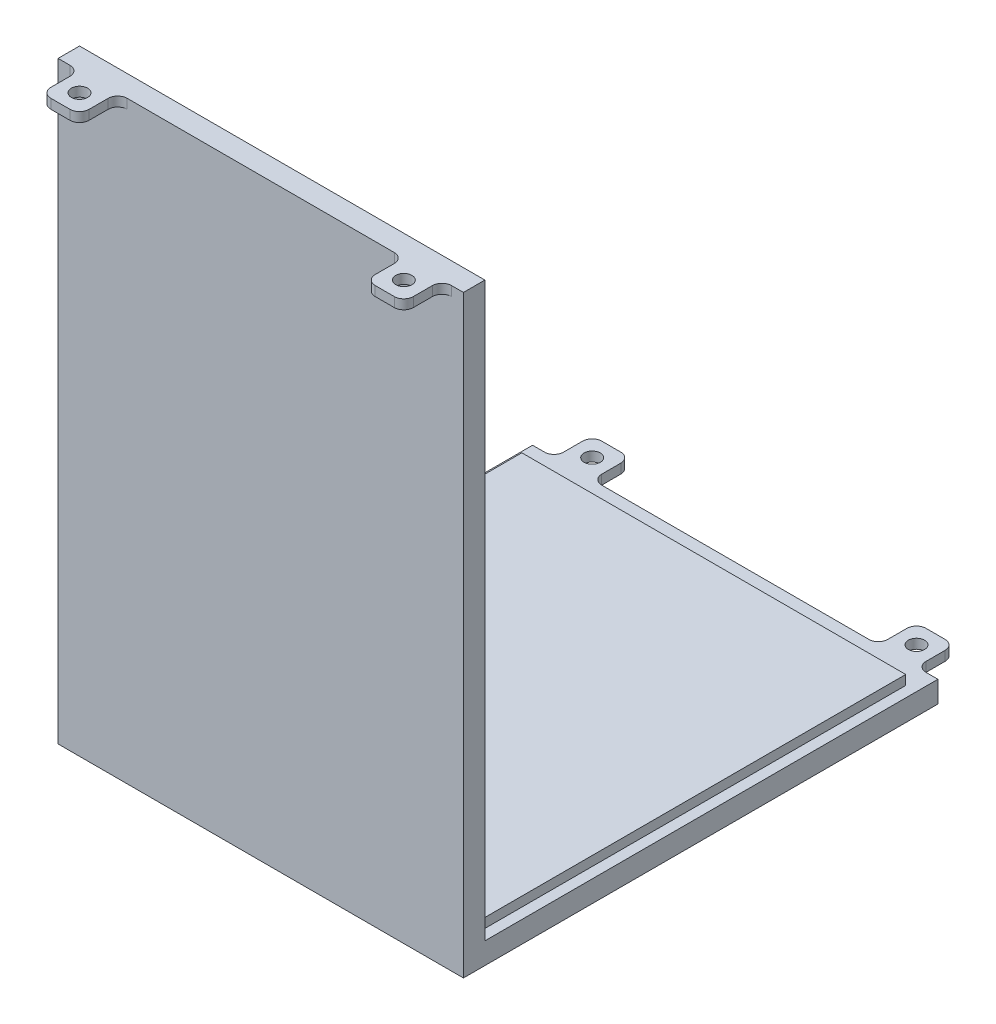
SolidWorks part; units mm, degrees
ref_plane "Front Plane" through (0, 0, 0) normal (1, 0, 0) x (0, 1, 0)
ref_plane "Top Plane" through (0, 0, 0) normal (0, 0, 1) x (0, 1, 0)
ref_plane "Right Plane" through (0, 0, 0) normal (0, 1, 0) x (-1, 0, 0)
sketch "Sketch1" plane through (0, 0, 0) normal (0, 0, 1) x (0, 1, 0)
  line L1 (0, 0) -> (124.5, 0)
  line L2 (0, 0) -> (0, 85)
  line L3 (0, 85) -> (124.5, 85)
  line L4 (124.5, 0) -> (124.5, 85)
  dimension "D1" = 85
  dimension "D2" = 124.5
extrude "Boss-Extrude1" add sketch "Sketch1" along normal blind 4.5
sketch "Sketch2" plane through (0, 0, 0) normal (0, 0, -1) x (1, 0, 0)
  line L0 (0, 0) -> (0, -124.5) construction
  line L1 (-85, 0) -> (0, 0)
  line L2 (-85, 0) -> (-85, -4.5)
  line L3 (-85, -4.5) -> (0, -4.5)
  line L4 (0, 0) -> (0, -4.5)
  dimension "D1" = 4.5
extrude "Boss-Extrude2" add sketch "Sketch2" along normal blind 95
sketch "Sketch3" plane through (0, 0, 0) normal (0, 0, -1) x (1, 0, 0)
  line L0 (-85, -4.5) -> (0, -4.5) construction
  line L1 (-82.75, -4.5) -> (-2.25, -4.5)
  line L2 (-82.75, -4.5) -> (-82.75, -6.5)
  line L3 (-82.75, -6.5) -> (-2.25, -6.5)
  line L4 (-2.25, -4.5) -> (-2.25, -6.5)
  line L5 (-42.5, -124.5) -> (-42.5, -4.5) construction
  line L6 (0, -124.5) -> (-85, -124.5) construction
  line L7 (-85, -124.5) -> (-85, -4.5) construction
  line L8 (0, 0) -> (0, -124.5) construction
  dimension "D1" = 2.25
  dimension "D2" = 2.25
  dimension "D3" = 2
extrude "Boss-Extrude3" add sketch "Sketch3" along normal offset from surface (90.5 mm away) 4.5 up to face at (-42.5, 2.25, -95)
sketch "Sketch4" plane through (0, 0, 4.5) normal (0, 0, 1) x (1, 0, 0)
  line L0 (-42.5, 124.5) -> (-42.5, 0) construction
  line L1 (0, 124.5) -> (-85, 124.5) construction
  line L2 (-85, 0) -> (0, 0) construction
  line L3 (-85, 124.5) -> (-85, 0) construction
  line L4 (-80.5, 124.5) -> (-72.5, 124.5)
  line L5 (-80.5, 124.5) -> (-80.5, 122.5)
  line L6 (-80.5, 122.5) -> (-72.5, 122.5)
  line L7 (-72.5, 124.5) -> (-72.5, 122.5)
  line L8 (-4.5, 122.5) -> (-12.5, 122.5)
  line L9 (-12.5, 124.5) -> (-12.5, 122.5)
  line L10 (-4.5, 124.5) -> (-12.5, 124.5)
  line L11 (-4.5, 124.5) -> (-4.5, 122.5)
  dimension "D1" = 4.5
  dimension "D2" = 2
  dimension "D3" = 8
extrude "Boss-Extrude4" add sketch "Sketch4" along normal blind 8
sketch "Sketch5" plane through (0, 0, -95) normal (0, 0, -1) x (1, 0, 0)
  line L0 (-42.5, 0) -> (-42.5, -4.5) construction
  line L1 (0, 0) -> (-85, 0) construction
  line L2 (-2.25, -4.5) -> (-82.75, -4.5) construction
  line L3 (-85, 0) -> (-85, -4.5) construction
  line L4 (-80.5, -4.5) -> (-72.5, -4.5)
  line L5 (-80.5, -4.5) -> (-80.5, -2.5)
  line L6 (-80.5, -2.5) -> (-72.5, -2.5)
  line L7 (-72.5, -4.5) -> (-72.5, -2.5)
  line L8 (-4.5, -2.5) -> (-12.5, -2.5)
  line L9 (-12.5, -4.5) -> (-12.5, -2.5)
  line L10 (-4.5, -4.5) -> (-12.5, -4.5)
  line L11 (-4.5, -4.5) -> (-4.5, -2.5)
  dimension "D1" = 4.5
  dimension "D2" = 8
  dimension "D3" = 2
extrude "Boss-Extrude5" add sketch "Sketch5" along normal blind 8
sketch "Sketch6" plane through (0, 124.5, 0) normal (0, 1, 0) x (-1, 0, 0)
  line L0 (12.5, 8.5) -> (4.5, 8.5) construction
  line L1 (12.5, 12.5) -> (12.5, 4.5) construction
  line L2 (4.5, 12.5) -> (4.5, 4.5) construction
  line L3 (8.5, 12.5) -> (8.5, 0) construction
  line L4 (4.5, 12.5) -> (12.5, 12.5) construction
  line L5 (0, 0) -> (85, 0) construction
  line L6 (42.5, 4.5) -> (42.5, 0) construction
  line L7 (12.5, 4.5) -> (72.5, 4.5) construction
  line L8 (82.75, 0) -> (2.25, 0) construction
  line L9 (2.25, -45.25) -> (82.75, -45.25) construction
  line L10 (2.25, -90.5) -> (2.25, 0) construction
  line L11 (82.75, -90.5) -> (82.75, 0) construction
  circle A0 centre (8.5, 8.5) radius 1.7
  circle A1 centre (76.5, 8.5) radius 1.7
  circle A2 centre (76.5, -99) radius 1.7
  circle A3 centre (8.5, -99) radius 1.7
  dimension "D1" = 3.4
extrude "Cut-Extrude1" cut sketch "Sketch6" against normal through all both and the other way through all
fillet "Fillet1" radius 2 16 edges at (-12.5, 3.5, -95) (-12.5, 3.5, -103) (-4.5, 3.5, -95) (-4.5, 3.5, -103) (-72.5, 3.5, -95) (-72.5, 3.5, -103) (-80.5, 3.5, -103) (-80.5, 3.5, -95) (-12.5, 123.5, 4.5) (-12.5, 123.5, 12.5) (-4.5, 123.5, 12.5) (-4.5, 123.5, 4.5) (-72.5, 123.5, 4.5) (-72.5, 123.5, 12.5) (-80.5, 123.5, 12.5) (-80.5, 123.5, 4.5)
